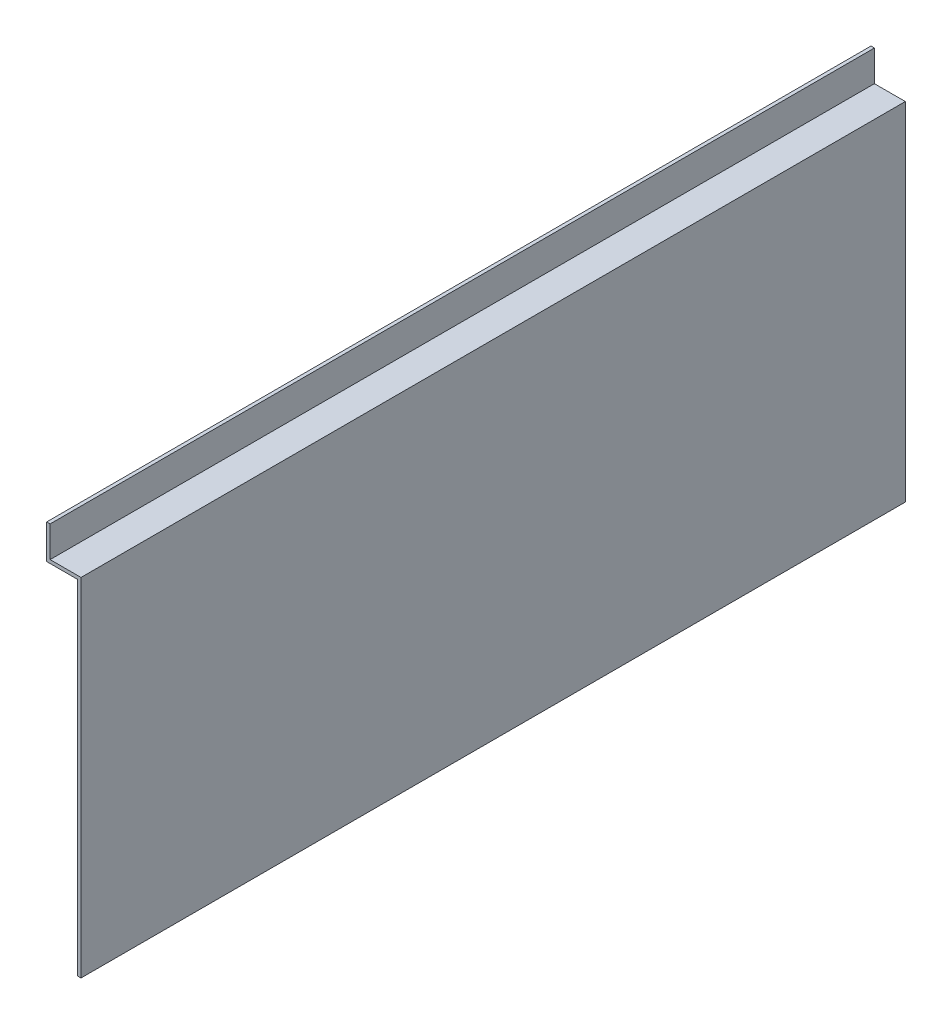
SolidWorks part; units mm, degrees
ref_plane "Alzado" through (0, 0, 0) normal (0, 0, 1) x (1, 0, 0)
ref_plane "Planta" through (0, 0, 0) normal (0, 1, 0) x (1, 0, 0)
ref_plane "Vista lateral" through (0, 0, 0) normal (1, 0, 0) x (0, 0, -1)
sketch "Croquis1" plane through (0, 0, 0) normal (0, 0, 1) x (1, 0, 0)
  line L0 (0, 0) -> (0, -10)
  line L1 (0, -10) -> (9, -10)
  line L2 (9, -10) -> (9, -110)
extrude "Extruir-Lámina1" add sketch "Croquis1" along normal blind 240 thin thin type one direction reverse wall 1
